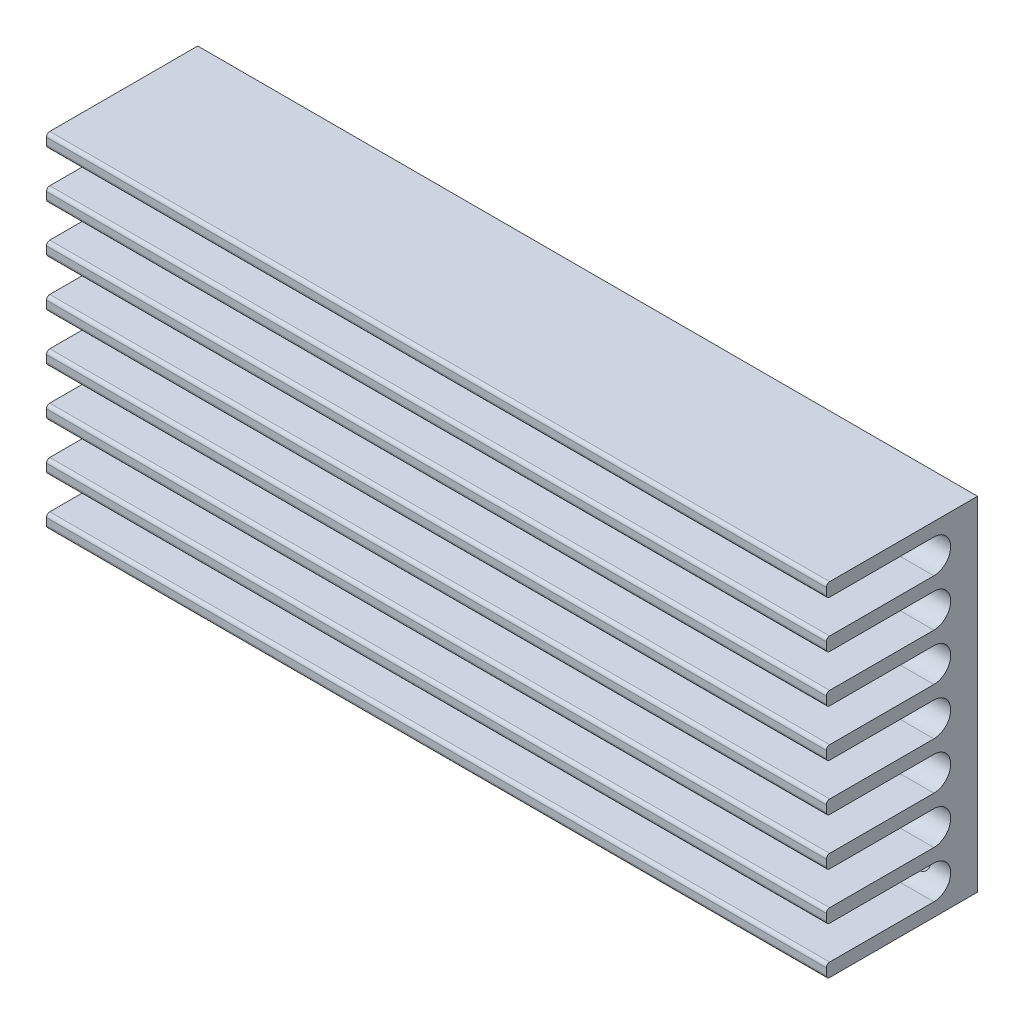
SolidWorks part; units mm, degrees
ref_plane "前视基准面" through (0, 0, 0) normal (0, 0, 1) x (1, 0, 0)
ref_plane "上视基准面" through (0, 0, 0) normal (0, 1, 0) x (1, 0, 0)
ref_plane "右视基准面" through (0, 0, 0) normal (1, 0, 0) x (0, 0, -1)
sketch "Sketch1" plane through (0, 0, 0) normal (1, 0, 0) x (0, 0, -1)
  line L1 (-11.25, 25.5) -> (11.25, 25.5)
  line L2 (-11.25, 25.5) -> (-11.25, -25.5)
  line L3 (-11.25, -25.5) -> (11.25, -25.5)
  line L4 (11.25, 25.5) -> (11.25, -25.5)
  line L5 (-11.25, 25.5) -> (11.25, -25.5) construction
  line L6 (-11.25, -25.5) -> (11.25, 25.5) construction
  point P0 (0, 0)
  dimension "D1" = 51
  dimension "D2" = 22.5
extrude "Boss-Extrude1" add sketch "Sketch1" along normal mid plane 116
sketch "Sketch2" plane through (-58, 0, 0) normal (-1, 0, 0) x (0, 0, 1)
  line L0 (-4.75, 2.5) -> (11.25, 2.5)
  line L1 (11.25, 25.5) -> (11.25, -25.5) construction
  line L2 (11.25, 2.5) -> (11.25, -2.5)
  line L3 (11.25, -2.5) -> (-4.75, -2.5)
  arc A0 (-4.75, 2.5) -> (-4.75, -2.5) centre (-4.75, 0) ccw
  dimension "D1" = 5
  dimension "D2" = 16
extrude "Cut-Extrude1" cut sketch "Sketch2" against normal up to next
pattern_linear "LPattern1" count 4 spacing 7 along (0, -1, 0) count 4 spacing 7 along (0, 1, 0) of "Cut-Extrude1"
fillet "Fillet1" radius 0.5 16 edges at (0, -25.5, 11.25) (0, -23.5, 11.25) (0, -18.5, 11.25) (0, -16.5, 11.25) (0, -11.5, 11.25) (0, -9.5, 11.25) (0, -4.5, 11.25) (0, -2.5, 11.25) (0, 2.5, 11.25) (0, 4.5, 11.25) (0, 9.5, 11.25) (0, 11.5, 11.25) (0, 16.5, 11.25) (0, 18.5, 11.25) (0, 23.5, 11.25) (0, 25.5, 11.25)
sketch "Sketch3" plane through (0, 0, -11.25) normal (0, 0, -1) x (-1, 0, 0)
  line L1 (-54, 21.5) -> (54, 21.5) construction
  line L2 (-54, 21.5) -> (-54, -21.5) construction
  line L3 (-54, -21.5) -> (54, -21.5) construction
  line L4 (54, 21.5) -> (54, -21.5) construction
  line L5 (-54, 21.5) -> (54, -21.5) construction
  line L6 (-54, -21.5) -> (54, 21.5) construction
  circle A0 centre (-54, 21.5) radius 1
  circle A1 centre (-54, -21.5) radius 1
  circle A2 centre (54, -21.5) radius 1
  circle A3 centre (54, 21.5) radius 1
  point P0 (0, 0)
  dimension "D3" = 2
  dimension "D1" = 43
  dimension "D2" = 108
extrude "Cut-Extrude2" cut sketch "Sketch3" against normal up to next
